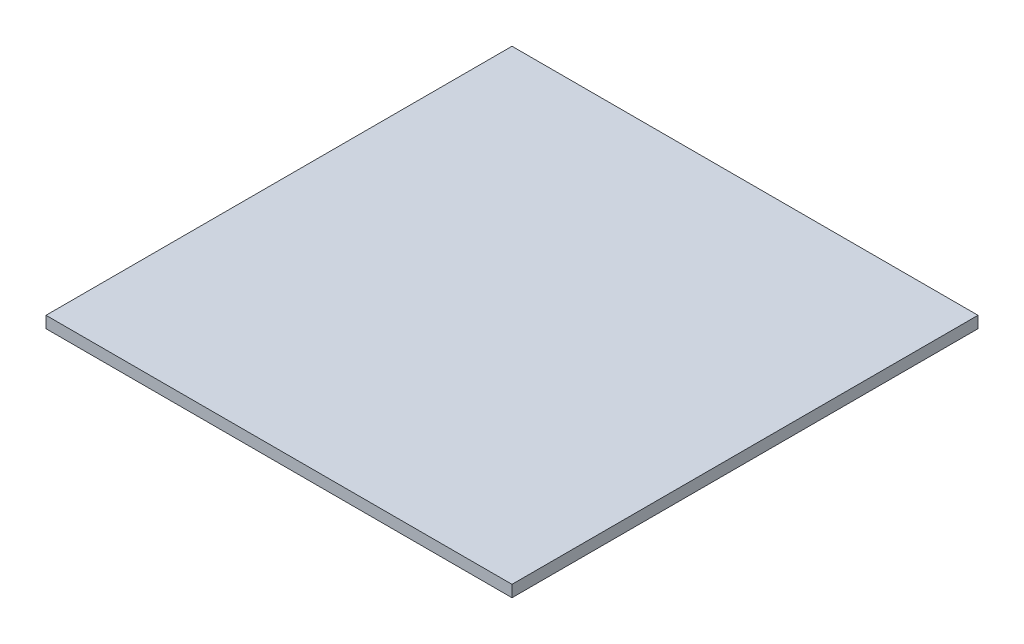
SolidWorks part; units mm, degrees
material "Glass"
ref_plane "Front Plane" through (0, 0, 0) normal (0, 0, 1) x (1, 0, 0)
ref_plane "Top Plane" through (0, 0, 0) normal (0, 1, 0) x (1, 0, 0)
ref_plane "Right Plane" through (0, 0, 0) normal (1, 0, 0) x (0, 0, -1)
sketch "Sketch1" plane through (0, 0, 0) normal (0, 1, 0) x (1, 0, 0)
  line L1 (0, 0) -> (200, 0)
  line L2 (0, 0) -> (0, 200)
  line L3 (0, 200) -> (200, 200)
  line L4 (200, 0) -> (200, 200)
  dimension "D1" = 200
  dimension "D2" = 200
extrude "Boss-Extrude1" add sketch "Sketch1" along normal blind 5
